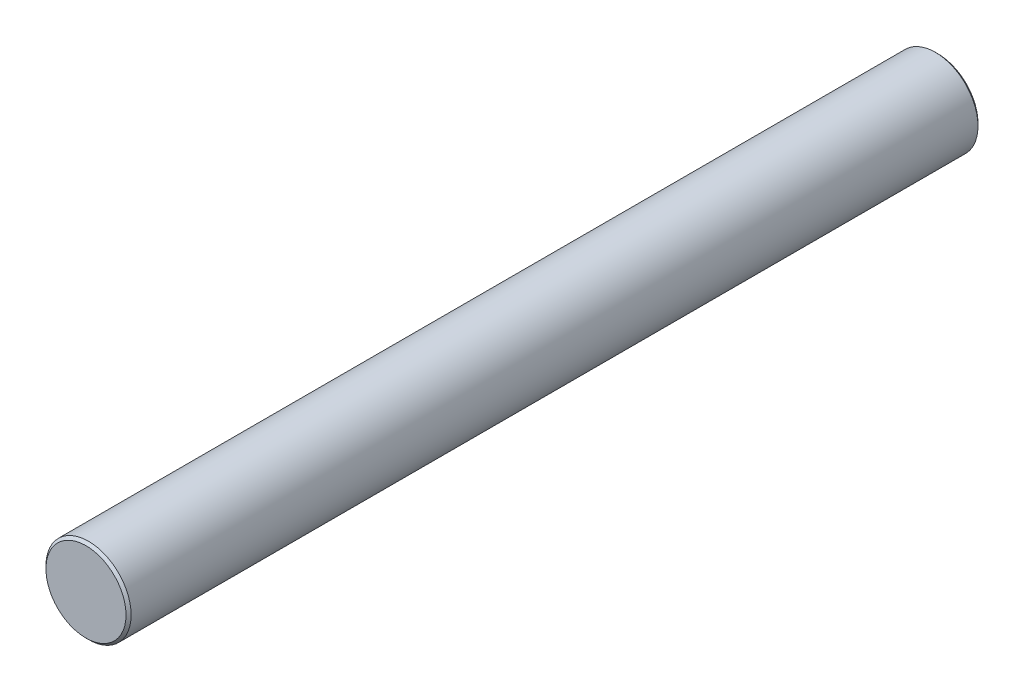
SolidWorks part; units mm, degrees
ref_plane "Płaszczyzna przednia" through (0, 0, 0) normal (0, 0, 1) x (1, 0, 0)
ref_plane "Płaszczyzna górna" through (0, 0, 0) normal (0, 1, 0) x (1, 0, 0)
ref_plane "Płaszczyzna prawa" through (0, 0, 0) normal (1, 0, 0) x (0, 0, -1)
sketch "Szkic1" plane through (0, 0, 0) normal (0, 0, 1) x (1, 0, 0)
  circle A0 centre (0, 0) radius 5
  dimension "D1" = 10
extrude "Dodanie-wyciągnięcie1" add sketch "Szkic1" along normal mid plane 100
chamfer "Sfazowanie1" distance 0.3 angle 45 2 edges at (5, 0, -50) (5, 0, 50)
